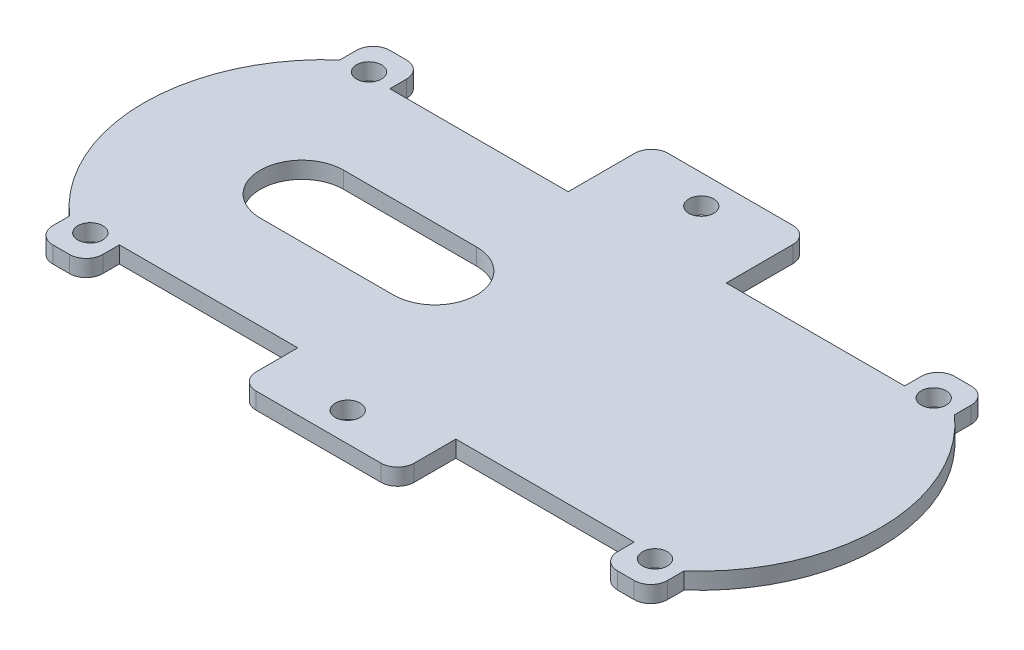
SolidWorks part; units mm, degrees
ref_plane "Front Plane" through (0, 0, 0) normal (0, 0, 1) x (1, 0, 0)
ref_plane "Top Plane" through (0, 0, 0) normal (0, 1, 0) x (1, 0, 0)
ref_plane "Right Plane" through (0, 0, 0) normal (1, 0, 0) x (0, 0, -1)
sketch "Sketch3" plane through (0, 0, 0) normal (0, 1, 0) x (1, 0, 0)
  line L0 (-9.2693, -10.6506) -> (-9.2693, -17.6506)
  line L1 (-9.2693, -17.6506) -> (9.7307, -17.6506)
  line L2 (9.7307, -17.6506) -> (9.7307, -10.6506)
  line L3 (9.7307, -10.6506) -> (31.1674, -10.6506)
  line L4 (31.1674, -10.6506) -> (31.1674, -14.6506)
  line L5 (31.1674, -14.6506) -> (37.1674, -14.6506)
  line L6 (37.1674, -14.6506) -> (37.1674, -10.6506)
  line L7 (37.1674, 21.8494) -> (37.1674, 25.8494)
  line L8 (37.1674, 25.8494) -> (31.1674, 25.8494)
  line L9 (31.1674, 25.8494) -> (31.1674, 21.8494)
  line L10 (31.1674, 21.8494) -> (9.7307, 21.8494)
  line L11 (9.7307, 21.8494) -> (9.7307, 31.8494)
  line L12 (9.7307, 31.8494) -> (-9.2693, 31.8494)
  line L13 (-9.2693, 31.8494) -> (-9.2693, 21.8494)
  line L14 (-9.2693, 21.8494) -> (-30.706, 21.8494)
  line L15 (-30.706, 21.8494) -> (-30.706, 25.8494)
  line L16 (-30.706, 25.8494) -> (-36.706, 25.8494)
  line L17 (-36.706, 25.8494) -> (-36.706, 21.8494)
  line L18 (-36.706, -10.6506) -> (-36.706, -14.6506)
  line L19 (-36.706, -14.6506) -> (-30.706, -14.6506)
  line L20 (-30.706, -14.6506) -> (-30.706, -10.6506)
  line L21 (-30.706, -10.6506) -> (-9.2693, -10.6506)
  circle A0 centre (-33.706, 22.3494) radius 1.5
  circle A1 centre (-33.706, -11.1506) radius 1.5
  circle A2 centre (34.1674, -11.1506) radius 1.5
  circle A3 centre (34.1674, 22.3494) radius 1.5
  circle A4 centre (0.2307, -14.1506) radius 1.5
  circle A5 centre (0.2307, 28.3494) radius 1.5
  arc A6 (37.1674, -10.6506) -> (37.1674, 21.8494) centre (22.7705, 5.5994) ccw
  arc A7 (-36.706, 21.8494) -> (-36.706, -10.6506) centre (-22.309, 5.5994) ccw
extrude "Boss-Extrude3" add sketch "Sketch3" along normal blind 2
sketch "Sketch4" plane through (0, 2, 0) normal (0, 1, 0) x (1, 0, 0)
  line L0 (-44.0193, 5.5994) -> (-41.0193, 5.5994) construction
  line L1 (-25.0193, 5.5994) -> (-9.0193, 5.5994) construction
  line L2 (-25.0193, 10.5994) -> (-9.0193, 10.5994)
  line L3 (-25.0193, 0.5994) -> (-9.0193, 0.5994)
  arc A0 (-36.706, 21.8494) -> (-36.706, -10.6506) centre (-22.309, 5.5994) ccw construction
  arc A1 (-25.0193, 10.5994) -> (-25.0193, 0.5994) centre (-25.0193, 5.5994) ccw
  arc A2 (-9.0193, 0.5994) -> (-9.0193, 10.5994) centre (-9.0193, 5.5994) ccw
  point P8 (-17.0193, 5.5994)
  dimension "D3" = 16
  dimension "D1" = 3
  dimension "D2" = 10
  dimension "D4" = 24
extrude "Cut-Extrude1" cut sketch "Sketch4" against normal blind 3
fillet "Fillet1" radius 2 12 edges at (37.1674, 1, 14.6506) (31.1674, 1, 14.6506) (9.7307, 1, 17.6506) (-9.2693, 1, 17.6506) (-30.706, 1, 14.6506) (-36.706, 1, 14.6506) (-30.706, 1, -25.8494) (-36.706, 1, -25.8494) (-9.2693, 1, -31.8494) (9.7307, 1, -31.8494) (37.1674, 1, -25.8494) (31.1674, 1, -25.8494)
